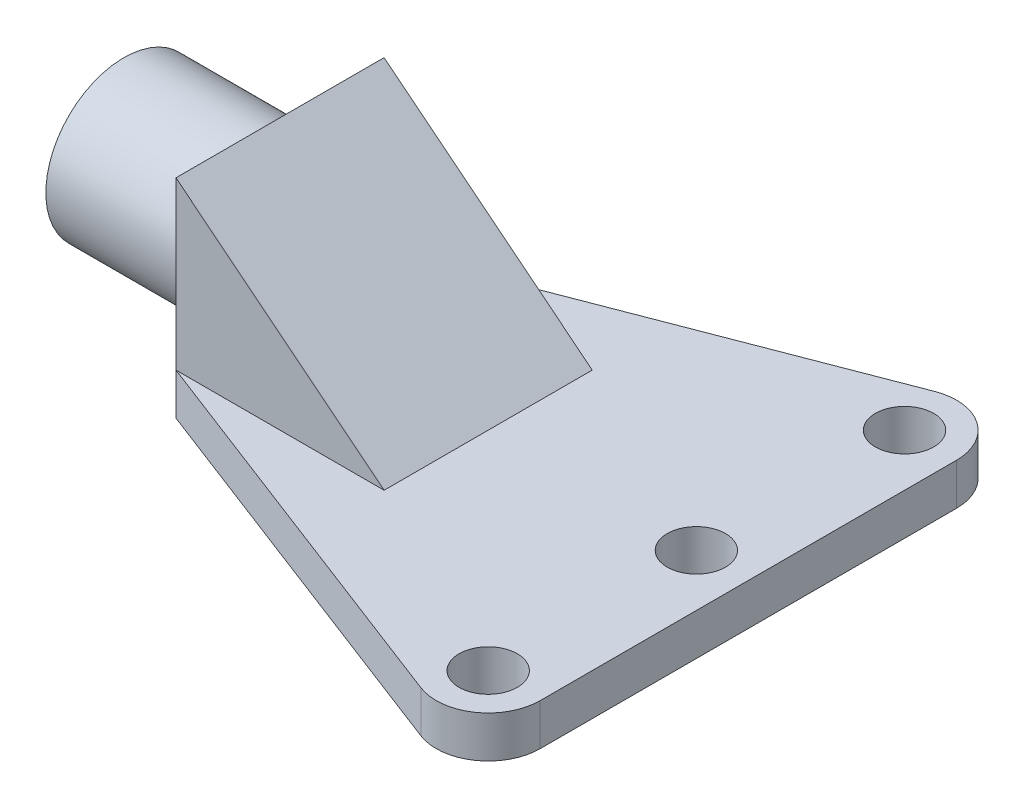
SolidWorks part; units mm, degrees
ref_plane "Front Plane" through (0, 0, 0) normal (0, 0, 1) x (1, 0, 0)
ref_plane "Top Plane" through (0, 0, 0) normal (0, 1, 0) x (1, 0, 0)
ref_plane "Right Plane" through (0, 0, 0) normal (1, 0, 0) x (0, 0, -1)
sketch "Sketch1" plane through (0, 0, 0) normal (0, 1, 0) x (1, 0, 0)
  line L0 (0, 0) -> (0, 25.4)
  line L1 (0, 0) -> (0, -25.4)
  line L2 (0, 0) -> (-38.1, 0)
  line L3 (-50.8, -12.7) -> (-2.2757, -31.3279)
  line L4 (-50.8, -12.7) -> (-25.4, -12.7)
  line L5 (-50.8, -12.7) -> (-50.8, 12.7)
  line L6 (-50.8, 12.7) -> (-25.4, 12.7)
  line L7 (-25.4, -12.7) -> (-25.4, 12.7)
  line L8 (-50.8, -12.7) -> (-25.4, 12.7) construction
  line L9 (-50.8, 12.7) -> (-25.4, -12.7) construction
  line L10 (-50.8, 12.7) -> (-2.2758, 31.3282)
  line L11 (0, 25.4) -> (6.35, 25.4)
  line L12 (6.35, 25.4) -> (6.3497, -25.4)
  circle A0 centre (0, 25.4) radius 3.302
  circle A1 centre (0, -25.4) radius 3.302
  arc A2 (-2.2757, -31.3279) -> (6.3497, -25.4) centre (0, -25.4) ccw
  arc A3 (6.35, 25.4) -> (-2.2758, 31.3282) centre (0, 25.4) ccw
sketch "Sketch2" plane through (0, 0, 0) normal (0, 1, 0) x (1, 0, 0)
  line L0 (-50.8, -12.7) -> (-25.4, -12.7)
  line L1 (-50.8, -12.7) -> (-50.8, 12.7)
  line L2 (-50.8, 12.7) -> (-25.4, 12.7)
  line L3 (-25.4, -12.7) -> (-25.4, 12.7)
extrude "Boss-Extrude1" add sketch "Sketch2" along normal blind 25.4
sketch "Sketch4" plane through (0, 0, 0) normal (0, 1, 0) x (1, 0, 0)
  line L0 (-50.8, -12.7) -> (-2.2757, -31.3279)
  line L1 (-50.8, -12.7) -> (-50.8, 12.7)
  line L2 (-50.8, 12.7) -> (-2.2758, 31.3282)
  line L3 (6.35, 25.4) -> (6.3497, -25.4)
  arc A0 (-2.2757, -31.3279) -> (6.3497, -25.4) centre (0, -25.4) ccw
  arc A1 (6.35, 25.4) -> (-2.2758, 31.3282) centre (0, 25.4) ccw
extrude "Boss-Extrude2" add sketch "Sketch4" along normal blind 5.08 separate body
sketch "Sketch5" plane through (0, 0, 0) normal (0, 1, 0) x (1, 0, 0)
  circle A0 centre (0, -25.4) radius 3.556
extrude "Cut-Extrude1" cut sketch "Sketch5" along normal up to next (5.08 mm away)
sketch "Sketch6" plane through (0, 0, 0) normal (0, 1, 0) x (1, 0, 0)
  circle A0 centre (0, 25.4) radius 3.556
extrude "Cut-Extrude2" cut sketch "Sketch6" along normal up to next (5.08 mm away)
sketch "Sketch7" plane through (0, 0, -12.7) normal (0, 0, -1) x (-1, 0, 0)
  line L0 (50.8, 25.4) -> (25.4, 5.08)
  line L1 (25.4, 25.4) -> (25.4, 0) construction
  line L2 (50.8, 5.08) -> (2.2757, 5.08) construction
  line L3 (25.4, 5.08) -> (25.4, 25.4)
  line L4 (25.4, 25.4) -> (50.8, 25.4)
sketch "Sketch8" plane through (0, 0, -12.7) normal (0, 0, -1) x (-1, 0, 0)
  line L0 (50.8, 25.4) -> (25.4, 5.08)
  line L1 (25.4, 5.08) -> (25.4, 25.4)
  line L2 (25.4, 25.4) -> (50.8, 25.4)
extrude "Cut-Extrude3" cut sketch "Sketch8" against normal up to next (25.4 mm away)
sketch "Sketch9" plane through (-50.8, 0, 0) normal (-1, 0, 0) x (0, 0, 1)
  line L0 (0, 25.4) -> (0, 0)
  line L1 (-12.7, 25.4) -> (12.7, 25.4) construction
  circle A0 centre (0, 12.7) radius 9.525
sketch "Sketch10" plane through (-50.8, 0, 0) normal (-1, 0, 0) x (0, 0, 1)
  circle A0 centre (0, 12.7) radius 9.525
extrude "Boss-Extrude3" add sketch "Sketch10" along normal blind 19.05
sketch "Sketch11" plane through (0, 0, 0) normal (0, 1, 0) x (1, 0, 0)
  circle A0 centre (0, 0) radius 3.302
sketch "Sketch12" plane through (0, 0, 0) normal (0, 1, 0) x (1, 0, 0)
  circle A0 centre (0, 0) radius 3.556
extrude "Cut-Extrude4" cut sketch "Sketch12" along normal up to next
